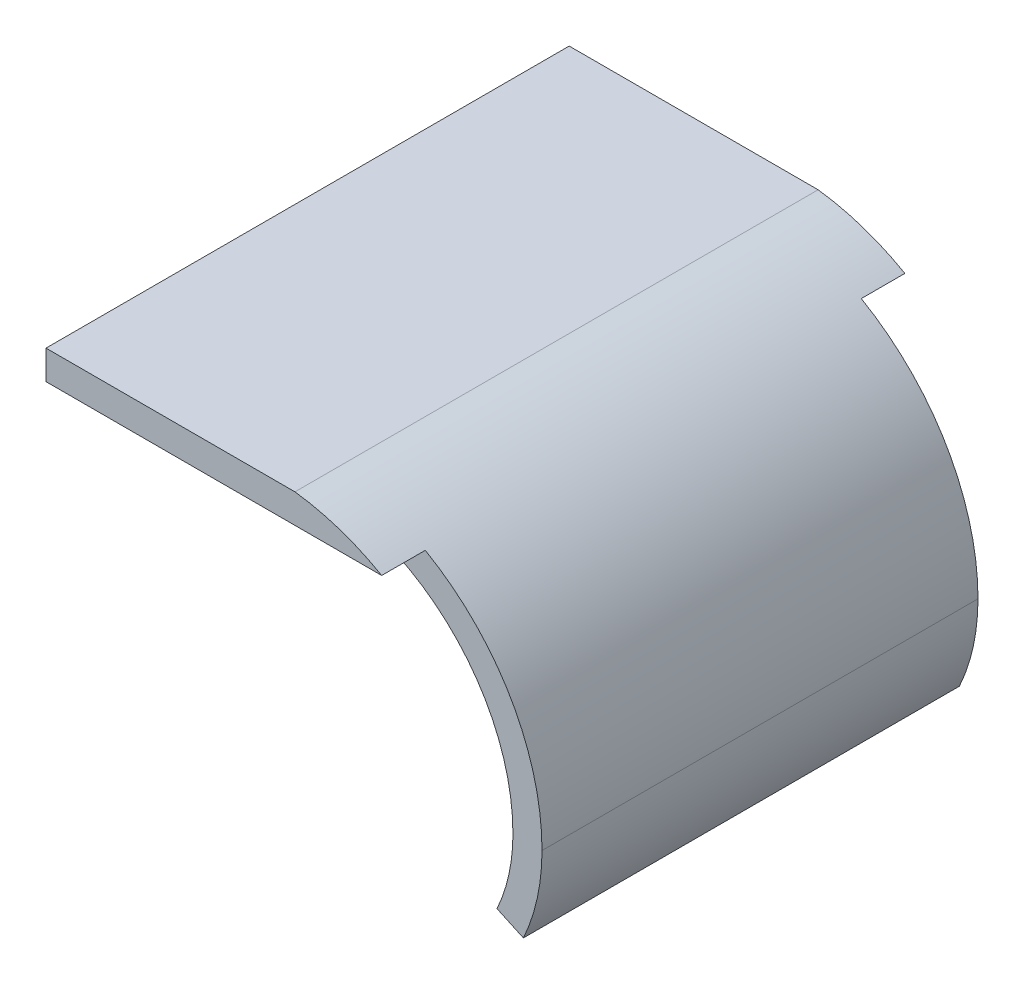
SolidWorks part; units mm, degrees
ref_plane "Front Plane" through (0, 0, 0) normal (0, 0, 1) x (1, 0, 0)
ref_plane "Top Plane" through (0, 0, 0) normal (0, 1, 0) x (1, 0, 0)
ref_plane "Right Plane" through (0, 0, 0) normal (1, 0, 0) x (0, 0, -1)
sketch "Sketch1" plane through (0, 0, 0) normal (0, 0, 1) x (1, 0, 0)
  line L3 (-0.0648, 6.9373) -> (-8.5648, 6.9373)
  line L4 (0, 7.9373) -> (-8.5648, 7.9373)
  line L5 (5.4511, -2.5071) -> (6.3596, -2.925)
  line L6 (-8.5648, 7.9373) -> (-8.5648, 6.9373)
  arc A0 (5.4511, -2.5071) -> (6, 0) centre (0, 0) ccw
  arc A1 (6, 0) -> (-0.0648, 6.9373) centre (-1, 0) ccw
  arc A2 (6.3596, -2.925) -> (7, 0) centre (0, 0) ccw
  arc A3 (7, 0) -> (0, 7.9373) centre (-1, 0) ccw
  arc A4 (0, -6) -> (6, 0) centre (0, 0) ccw construction
  arc A5 (0, -7) -> (7, 0) centre (0, 0) ccw construction
  point P15 (7, 0)
  point P16 (6, 0)
  point P17 (0, 0)
  dimension "D1" = 12
  dimension "D2" = 14
  dimension "D3" = 1
  dimension "D4" = 8.5
  dimension "D5" = 5.4511
extrude "Boss-Extrude1" add sketch "Sketch1" along normal mid plane 18
sketch "Sketch2" plane through (0, 0, 9) normal (0, 0, 1) x (1, 0, 0)
  line L0 (5.4511, -2.5071) -> (6.3596, -2.925) construction
  line L1 (5.4511, -2.5071) -> (6.3596, -2.925)
  line L2 (-0.0648, 6.9373) -> (2.9843, 6.9373)
  arc A0 (6.3596, -2.925) -> (7, 0) centre (0, 0) ccw construction
  arc A1 (5.4511, -2.5071) -> (6, 0) centre (0, 0) ccw construction
  arc A2 (7, 0) -> (0, 7.9373) centre (-1, 0) ccw construction
  arc A3 (6, 0) -> (-0.0648, 6.9373) centre (-1, 0) ccw construction
  arc A4 (6.3596, -2.925) -> (7, 0) centre (0, 0) ccw
  arc A5 (5.4511, -2.5071) -> (6, 0) centre (0, 0) ccw
  arc A6 (7, 0) -> (2.9843, 6.9373) centre (-1, 0) ccw
  arc A7 (6, 0) -> (-0.0648, 6.9373) centre (-1, 0) ccw
extrude "Cut-Extrude1" cut sketch "Sketch2" against normal blind 1.5
mirror "Mirror1" about plane through (0, 0, 0) normal (0, 0, 1) of "Cut-Extrude1"
